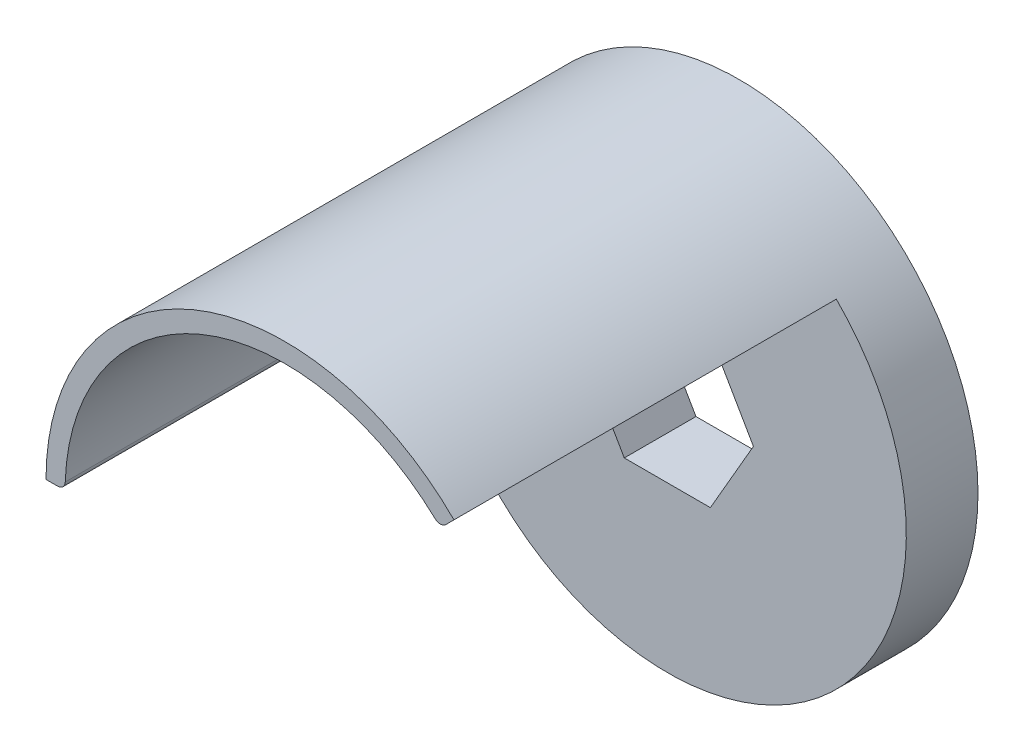
SolidWorks part; units mm, degrees
ref_plane "Front Plane" through (0, 0, 0) normal (0, 0, 1) x (1, 0, 0)
ref_plane "Top Plane" through (0, 0, 0) normal (0, 1, 0) x (1, 0, 0)
ref_plane "Right Plane" through (0, 0, 0) normal (1, 0, 0) x (0, 0, -1)
sketch "Sketch1" plane through (0, 0, 0) normal (0, 0, 1) x (1, 0, 0)
  line L1 (5.7192, 0) -> (2.8596, 4.953)
  line L2 (2.8596, 4.953) -> (-2.8596, 4.953)
  line L3 (-2.8596, 4.953) -> (-5.7192, 0)
  line L4 (-5.7192, 0) -> (-2.8596, -4.953)
  line L5 (-2.8596, -4.953) -> (2.8596, -4.953)
  line L6 (2.8596, -4.953) -> (5.7192, 0)
  circle A0 centre (0, 0) radius 15.875
  circle A1 centre (0, 0) radius 4.953 construction
  point P3 (0, 0)
  dimension "D1" = 31.75
  dimension "D2" = 9.906
extrude "Boss-Extrude1" add sketch "Sketch1" along normal blind 4.7625
sketch "Sketch2" plane through (0, 0, 4.7625) normal (0, 0, 1) x (1, 0, 0)
  line L0 (-14.605, 0) -> (-15.875, 0)
  line L1 (10.3273, 10.3273) -> (11.2253, 11.2253)
  circle A0 centre (0, 0) radius 14.605
  circle A1 centre (0, 0) radius 15.875
  circle A4 centre (0, 0) radius 15.875 construction
  point P10 (12.0727, 8.2192)
  circle M4 centre (0, 0) radius 15.875
  dimension "D1" = 29.21
  dimension "D2" = 135
extrude "Boss-Extrude2" add sketch "Sketch2" along normal blind 25.4 contours A0 L1 L0 M4
fillet "Fillet1" radius 0.508 2 edges at (10.3273, 10.3273, 17.4625) (-14.605, 0, 17.4625)
